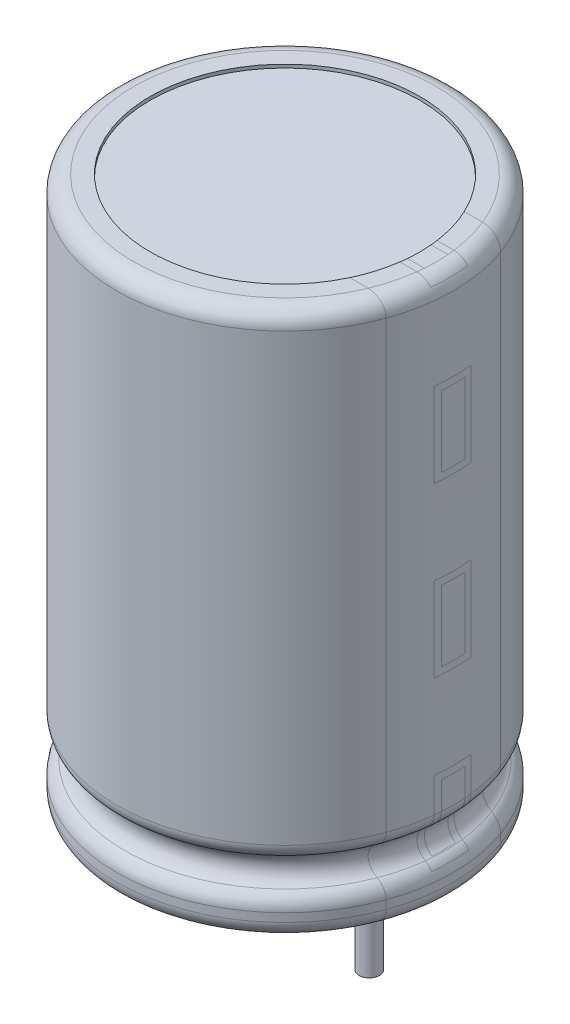
SolidWorks part; units mm, degrees
ref_plane "Front Plane" through (0, 0, 0) normal (0, 0, 1) x (1, 0, 0)
ref_plane "Top Plane" through (0, 0, 0) normal (0, 1, 0) x (1, 0, 0)
ref_plane "Right Plane" through (0, 0, 0) normal (1, 0, 0) x (0, 0, -1)
sketch "Sketch1" plane through (0, 0, 0) normal (0, 1, 0) x (1, 0, 0)
  line L0 (-2.5, 0) -> (2.5, 0) construction
  circle A0 centre (-2.5, 0) radius 0.3
  circle A1 centre (2.5, 0) radius 0.3
  dimension "D3" = 0.6
  dimension "D1" = 5
extrude "Boss-Extrude1" add sketch "Sketch1" against normal blind 3 and the other way blind 1
sketch "Sketch3" plane through (0, 0, 0) normal (0, 0, 1) x (1, 0, 0)
  line L1 (0, 0.1) -> (0, 16.2) construction
  line L2 (5, 0.5) -> (5, 0.75)
  line L3 (0, 0.1) -> (4, 0.1)
  line L4 (4, 16.2) -> (4.5, 16.2)
  line L5 (4, 0) -> (4.5, 0)
  line L6 (0, 16.1) -> (4, 16.1)
  line L7 (5, 2.4821) -> (5, 15.7)
  line L8 (4, 16.1) -> (4, 16.2)
  line L9 (5, 2.4821) -> (5, 16.2) construction
  line L10 (4, 0) -> (4, 0.1)
  line L11 (0, 16.1) -> (5, 16.1) construction
  line L12 (0, 16.2) -> (5, 16.2) construction
  line L13 (4, 2.4821) -> (4, 16.2) construction
  line L14 (0, 0.1) -> (0, 16.1)
  line L17 (0, 0.1) -> (5, 0.1) construction
  line L18 (0, 0) -> (5, 0) construction
  arc A0 (4.75, 2.049) -> (4.75, 1.183) centre (5, 1.616) ccw
  arc A1 (5, 0.75) -> (4.75, 1.183) centre (4.5, 0.75) ccw
  arc A2 (5, 2.4821) -> (4.75, 2.049) centre (4.5, 2.4821) cw
  arc A3 (5, 15.7) -> (4.5, 16.2) centre (4.5, 15.7) ccw
  arc A4 (4.5, 0) -> (5, 0.5) centre (4.5, 0.5) ccw
  point P1 (0, 0)
  point P13 (5, 2.116)
  point P32 (4.5, 1.616)
  dimension "D2" = 0.5
  dimension "D1" = 0.5
  dimension "D9" = 8
  dimension "D3" = 16
  dimension "D6" = 9
  dimension "D7" = 0.1
  dimension "D8" = 1
  dimension "D10" = 0.25
  dimension "D4" = 10
  dimension "D5" = 1
revolve "Revolve1" add sketch "Sketch3" angle 360 about L14
sketch "Sketch4" plane through (0, 0, 0) normal (1, 0, 0) x (0, 0, -1)
  line L0 (-4.5, 0) -> (4.5, 0) construction
  line L1 (-1.7, 0) -> (1.7, 0)
  line L2 (0, 0) -> (0, 16.2) construction
  line L3 (-1.7, 16.2) -> (1.7, 16.2)
  line L4 (1.7, 0) -> (1.7, 16.2)
  line L5 (4, 16.2) -> (-4, 16.2) construction
  line L6 (-1.7, 0) -> (-1.7, 16.2)
  line L7 (-0.35, 13.3) -> (-0.35, 11.2)
  line L8 (-0.35, 13.3) -> (0.35, 13.3)
  line L9 (0, 13.3) -> (0, 11.2) construction
  line L10 (-0.35, 11.2) -> (0.35, 11.2)
  line L11 (0.35, 13.3) -> (0.35, 11.2)
  line L12 (0.55, 13.5) -> (0.55, 11)
  line L13 (-0.55, 11) -> (0.55, 11)
  line L14 (-0.55, 13.5) -> (-0.55, 11)
  line L15 (-0.55, 13.5) -> (0.55, 13.5)
  line L16 (0, 0) -> (0, -3.7489) construction
  line L17 (-0.35, 8.3) -> (-0.35, 6.2)
  line L18 (-0.35, 8.3) -> (0.35, 8.3)
  line L19 (-0.35, 6.2) -> (0.35, 6.2)
  line L20 (0.35, 8.3) -> (0.35, 6.2)
  line L21 (0.55, 8.5) -> (0.55, 6)
  line L22 (-0.55, 6) -> (0.55, 6)
  line L23 (-0.55, 8.5) -> (-0.55, 6)
  line L24 (-0.55, 8.5) -> (0.55, 8.5)
  line L25 (0, 8.3) -> (0, 6.2) construction
  line L26 (-0.35, 3.3) -> (-0.35, 1.2)
  line L27 (-0.35, 3.3) -> (0.35, 3.3)
  line L28 (-0.35, 1.2) -> (0.35, 1.2)
  line L29 (0.35, 3.3) -> (0.35, 1.2)
  line L30 (0.55, 3.5) -> (0.55, 1)
  line L31 (-0.55, 1) -> (0.55, 1)
  line L32 (-0.55, 3.5) -> (-0.55, 1)
  line L33 (-0.55, 3.5) -> (0.55, 3.5)
  line L34 (0, 3.3) -> (0, 1.2) construction
  line L35 (-0.55, 18.5) -> (0.55, 18.5)
  line L36 (-0.55, 18.5) -> (-0.55, 16)
  line L37 (-0.35, 18.3) -> (0.35, 18.3)
  line L38 (0.35, 18.3) -> (0.35, 16.2)
  line L39 (0.55, 18.5) -> (0.55, 16)
  line L40 (-0.35, 18.3) -> (-0.35, 16.2)
  line L41 (-0.35, 16.2) -> (0.35, 16.2)
  line L42 (-0.55, 16) -> (0.55, 16)
  line L51 (-0.55, 11) -> (-0.55, 8.5) construction
  line L52 (-0.55, 13.5) -> (-0.55, 16) construction
  point P64 (0, 18.3)
  dimension "D5" = 3.4
  dimension "D6" = 0.2
  dimension "D7" = 1.1
  dimension "D8" = 2.1
  dimension "D1" = 0.7
  dimension "D9" = 1
  dimension "D10" = 2.5
  dimension "D2" = 3
  dimension "D3" = 2
split line "Split Line1"
